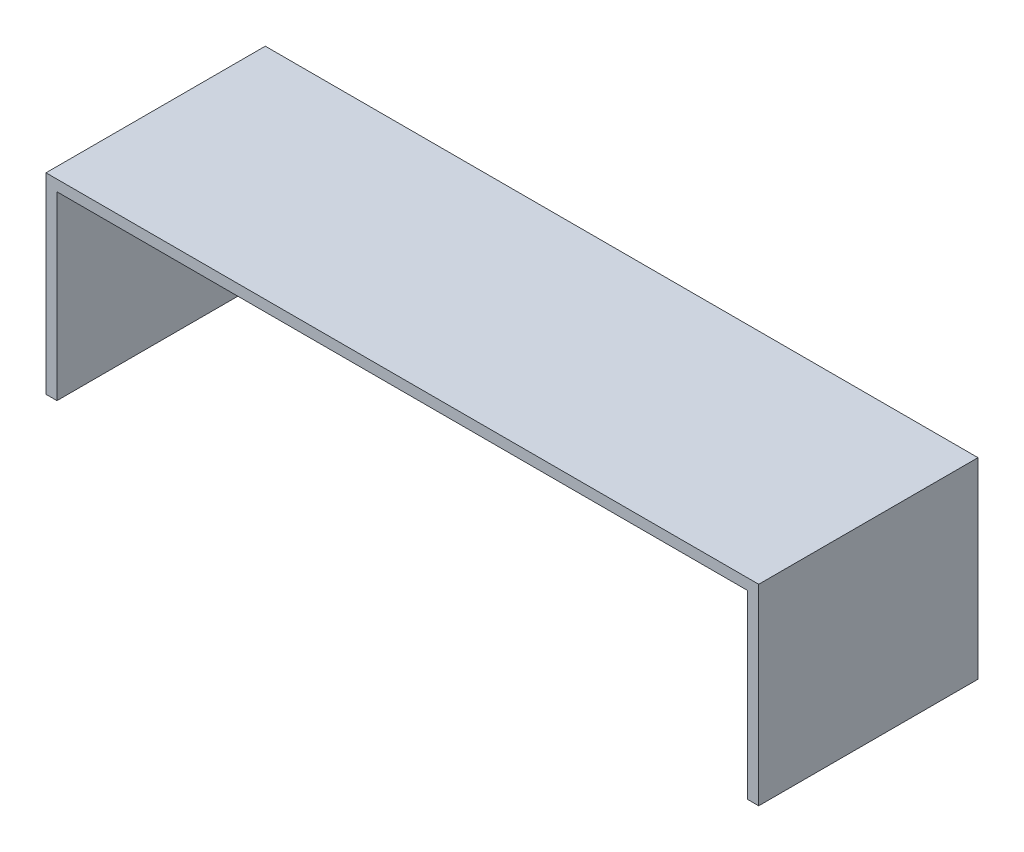
SolidWorks part; units mm, degrees
ref_plane "Front Plane" through (0, 0, 0) normal (0, 0, 1) x (1, 0, 0)
ref_plane "Top Plane" through (0, 0, 0) normal (0, 1, 0) x (1, 0, 0)
ref_plane "Right Plane" through (0, 0, 0) normal (1, 0, 0) x (0, 0, -1)
sketch "Sketch1" plane through (0, 0, 0) normal (0, 1, 0) x (1, 0, 0)
  line L1 (0, 0) -> (130, 0)
  line L2 (0, 0) -> (0, 40)
  line L3 (0, 40) -> (130, 40)
  line L4 (130, 0) -> (130, 40)
  dimension "D1" = 130
  dimension "D2" = 40
extrude "Boss-Extrude1" add sketch "Sketch1" along normal blind 2
sketch "Sketch2" plane through (0, 0, 0) normal (-1, 0, 0) x (0, 0, 1)
  line L1 (-40, 2) -> (0, 2)
  line L2 (-40, 2) -> (-40, -33)
  line L3 (-40, -33) -> (0, -33)
  line L4 (0, 2) -> (0, -33)
  dimension "D1" = 40
  dimension "D2" = 35
extrude "Boss-Extrude2" add sketch "Sketch2" against normal blind 2
ref_plane "Plane1" through (65, 0, 0) normal (1, 0, 0) x (0, 0, -1)
mirror "Mirror1" about plane through (65, 0, 0) normal (1, 0, 0) of "Boss-Extrude2"
